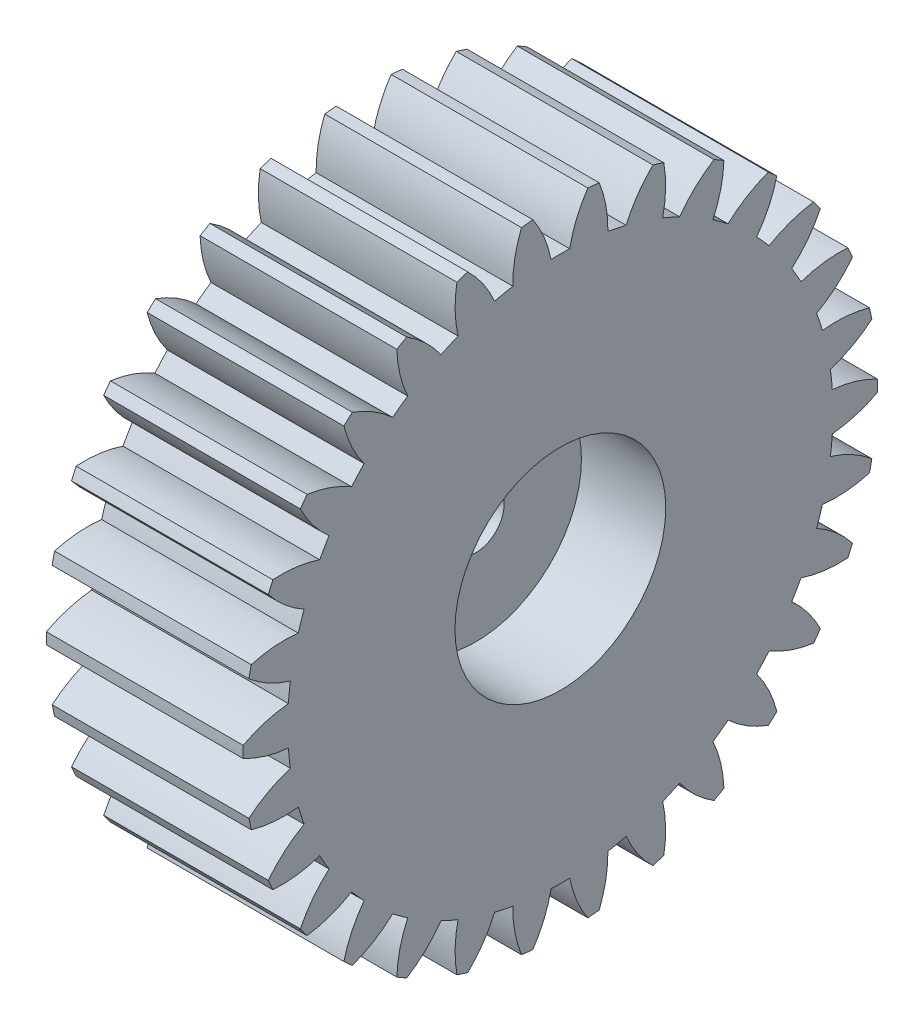
SolidWorks part; units mm, degrees
ref_plane "Alzado" through (0, 0, 0) normal (0, 0, 1) x (1, 0, 0)
ref_plane "Planta" through (0, 0, 0) normal (0, 1, 0) x (1, 0, 0)
ref_plane "Vista lateral" through (0, 0, 0) normal (1, 0, 0) x (0, 0, -1)
sketch "Croquis1" plane through (0, 0, 0) normal (0, 0, 1) x (1, 0, 0)
  line L0 (0, 0) -> (-50000, 0) construction
  line L1 (0, 11.25) -> (0, 3)
  line L2 (0, 3) -> (-5, 3)
  line L3 (-12, 7) -> (-12, 33.8671)
  line L4 (-12, 33.8671) -> (9, 33.8671)
  line L5 (9, 33.8671) -> (9, 11.25)
  line L6 (9, 11.25) -> (0, 11.25)
  line L7 (0, 0) -> (0, 50000) construction
  line L8 (-12, 7) -> (-5, 7)
  line L9 (-5, 7) -> (-5, 3)
  dimension "D1" = 33.8671
  dimension "D2" = 12
  dimension "D3" = 21
  dimension "D4" = 3
  dimension "D5" = 11.25
  dimension "D6" = 7
  dimension "D7" = 7
revolve "Revolución1" add sketch "Croquis1" angle 360 about L0
sketch "Croquis2" plane through (9, 0, 0) normal (1, 0, 0) x (0, 0, -1)
  line L0 (0, 0) -> (0, 50000) construction
  circle A0 centre (0, 0) radius 31.75 construction
  circle A1 centre (0, 0) radius 29.8348 construction
  arc A2 (2.9489, 33.7627) -> (-2.9489, 33.7627) centre (0, 0) ccw
  arc A3 (0.9956, 29.0863) -> (-0.9957, 29.0863) centre (0, 0) ccw
  arc A4 (-0.9957, 29.0863) -> (-2.9489, 33.7627) centre (-13.4556, 26.6283) ccw
  arc A5 (2.9489, 33.7627) -> (0.9956, 29.0863) centre (13.4597, 26.6262) ccw
  point P8 (0, 33.8912)
  dimension "D1" = 59.6697
  dimension "D2" = 63.5
  dimension "D3" = 33.8912
  dimension "D4" = 29.1033
  dimension "D7" = 12.7
  dimension "D8" = 12.7045
  dimension "D5" = 5.8979
  dimension "D6" = 1.9914
extrude "Cortar-Extruir1" cut sketch "Croquis2" against normal through all
pattern_circular "MatrizC1" count 30 over 360 about axis through (0, 0, 0) along (1, 0, 0) of "Cortar-Extruir1"
scale "Escala1" scale about centroid uniform scaling yes scale factor 0.25
